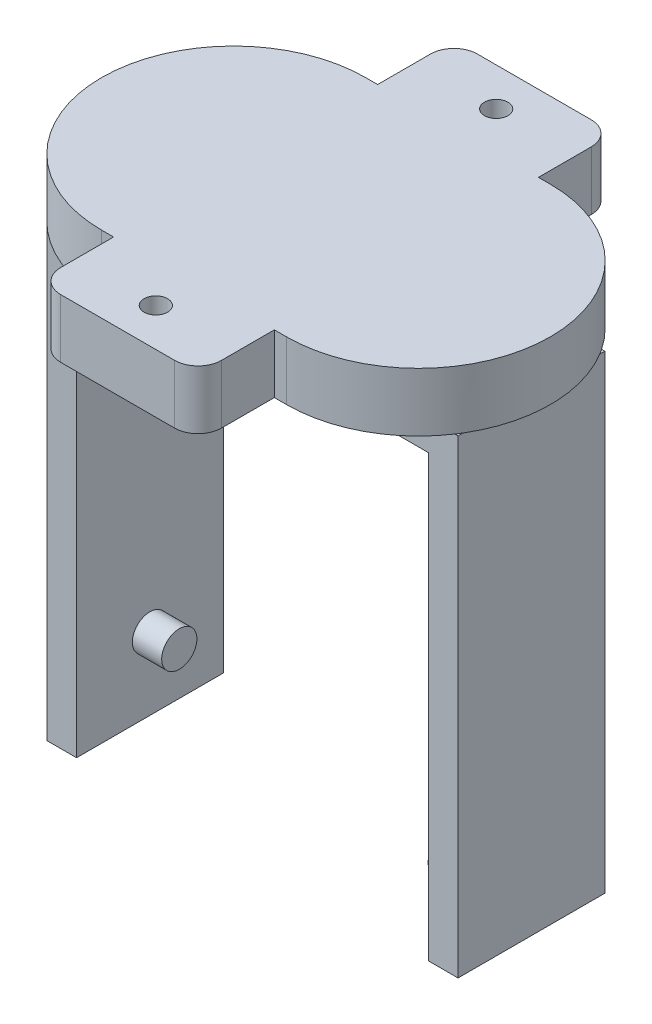
SolidWorks part; units mm, degrees
ref_plane "前基準面" through (0, 0, 0) normal (0, 0, 1) x (1, 0, 0)
ref_plane "上基準面" through (0, 0, 0) normal (0, 1, 0) x (1, 0, 0)
ref_plane "右基準面" through (0, 0, 0) normal (1, 0, 0) x (0, 0, -1)
sketch "草圖1" plane through (0, 0, 0) normal (1, 0, 0) x (0, 0, -1)
  line L1 (-12.4317, 21.2432) -> (12.5683, 21.2432)
  line L2 (-12.4317, 21.2432) -> (-12.4317, -58.7568)
  line L3 (-12.4317, -58.7568) -> (12.5683, -58.7568)
  line L4 (12.5683, 21.2432) -> (12.5683, -58.7568)
  dimension "D1" = 25
  dimension "D2" = 80
extrude "填料-伸長1" add sketch "草圖1" along normal blind 5
sketch "草圖8" plane through (5, 0, 0) normal (1, 0, 0) x (0, 0, -1)
  line L0 (12.5683, -58.7568) -> (12.5683, 21.2432) construction
  line L1 (-12.4317, 21.2432) -> (12.5683, 21.2432)
  line L2 (-12.4317, 21.2432) -> (-12.4317, 16.2432)
  line L3 (-12.4317, 16.2432) -> (12.5683, 16.2432)
  line L4 (12.5683, 21.2432) -> (12.5683, 16.2432)
  dimension "D1" = 5
extrude "填料-伸長6" add sketch "草圖8" along normal blind 60
sketch "草圖9" plane through (65, 0, 0) normal (1, 0, 0) x (0, 0, -1)
  line L1 (-12.4317, 21.2432) -> (12.5683, 21.2432)
  line L2 (-12.4317, 21.2432) -> (-12.4317, -58.7568)
  line L3 (-12.4317, -58.7568) -> (12.5683, -58.7568)
  line L4 (12.5683, 21.2432) -> (12.5683, -58.7568)
  dimension "D1" = 25
  dimension "D2" = 80
extrude "填料-伸長7" add sketch "草圖9" along normal blind 5
sketch "草圖10" plane through (65, 0, 0) normal (-1, 0, 0) x (0, 0, 1)
  line L1 (12.4317, 16.2432) -> (12.4317, -58.7568) construction
  line L2 (12.4317, -58.7568) -> (-12.5683, -58.7568) construction
  circle A0 centre (-0.0683, -46.4568) radius 10.3
  dimension "D1" = 20.6
  dimension "D2" = 12.5
  dimension "D3" = 12.3
extrude "填料-伸長9" add sketch "草圖10" along normal blind 2.3
sketch "草圖12" plane through (62.7, 0, 0) normal (-1, 0, 0) x (0, 0, 1)
  circle A0 centre (-0.0683, -46.4568) radius 4.35
  circle A1 centre (-0.0683, -46.4568) radius 3
  dimension "D1" = 8.7
  dimension "D2" = 6
extrude "填料-伸長10" add sketch "草圖12" along normal blind 3.15
sketch "草圖13" plane through (5, 0, 0) normal (1, 0, 0) x (0, 0, -1)
  line L0 (12.5683, -58.7568) -> (12.5683, 16.2432) construction
  line L1 (-12.4317, -58.7568) -> (12.5683, -58.7568) construction
  circle A0 centre (0.0683, -46.4568) radius 3
  dimension "D1" = 6
  dimension "D2" = 12.5
  dimension "D3" = 12.3
extrude "填料-伸長11" add sketch "草圖13" along normal blind 5
sketch "草圖15" plane through (0, 21.2432, 0) normal (0, 1, 0) x (1, 0, 0)
  line L0 (19.25, 0.0683) -> (50.75, 0.0683) construction
  line L1 (19.25, 22.5683) -> (50.75, 22.5683)
  line L2 (19.25, -22.4317) -> (50.75, -22.4317)
  line L3 (70, 12.5683) -> (0, 12.5683) construction
  line L5 (70, 12.5683) -> (70, -12.4317) construction
  line L8 (48.7, -22.4317) -> (21.3, -22.4317)
  line L9 (48.7, -22.4317) -> (48.7, -31.4317)
  line L10 (44.7, -35.4317) -> (25.3, -35.4317)
  line L11 (21.3, -22.4317) -> (21.3, -31.4317)
  line L12 (21.3, 22.5683) -> (48.7, 22.5683)
  line L13 (21.3, 22.5683) -> (21.3, 31.5683)
  line L14 (25.3, 35.5683) -> (44.7, 35.5683)
  line L15 (48.7, 22.5683) -> (48.7, 31.5683)
  arc A0 (19.25, 22.5683) -> (19.25, -22.4317) centre (19.25, 0.0683) ccw
  arc A1 (50.75, -22.4317) -> (50.75, 22.5683) centre (50.75, 0.0683) ccw
  circle A2 centre (35, -28.9317) radius 2
  circle A3 centre (35, 29.0683) radius 2
  arc A4 (44.7, 35.5683) -> (48.7, 31.5683) centre (44.7, 31.5683) cw
  arc A5 (25.3, 35.5683) -> (21.3, 31.5683) centre (25.3, 31.5683) ccw
  arc A6 (21.3, -31.4317) -> (25.3, -35.4317) centre (25.3, -31.4317) ccw
  arc A7 (48.7, -31.4317) -> (44.7, -35.4317) centre (44.7, -31.4317) cw
  point P2 (35, 0.0683)
  point P27 (21.3, 35.5683)
  point P30 (21.3, -35.4317)
  point P33 (48.7, -35.4317)
  dimension "D1" = 45
  dimension "D4" = 19.25
  dimension "D8" = 4
  dimension "D11" = 4
  dimension "D13" = 4
  dimension "D2" = 31.5
  dimension "D3" = 10
  dimension "D5" = 13
  dimension "D6" = 27.4
  dimension "D7" = 2.05
  dimension "D9" = 6.5
  dimension "D10" = 13
  dimension "D12" = 6.5
extrude "填料-伸長12" add sketch "草圖15" along normal blind 10
